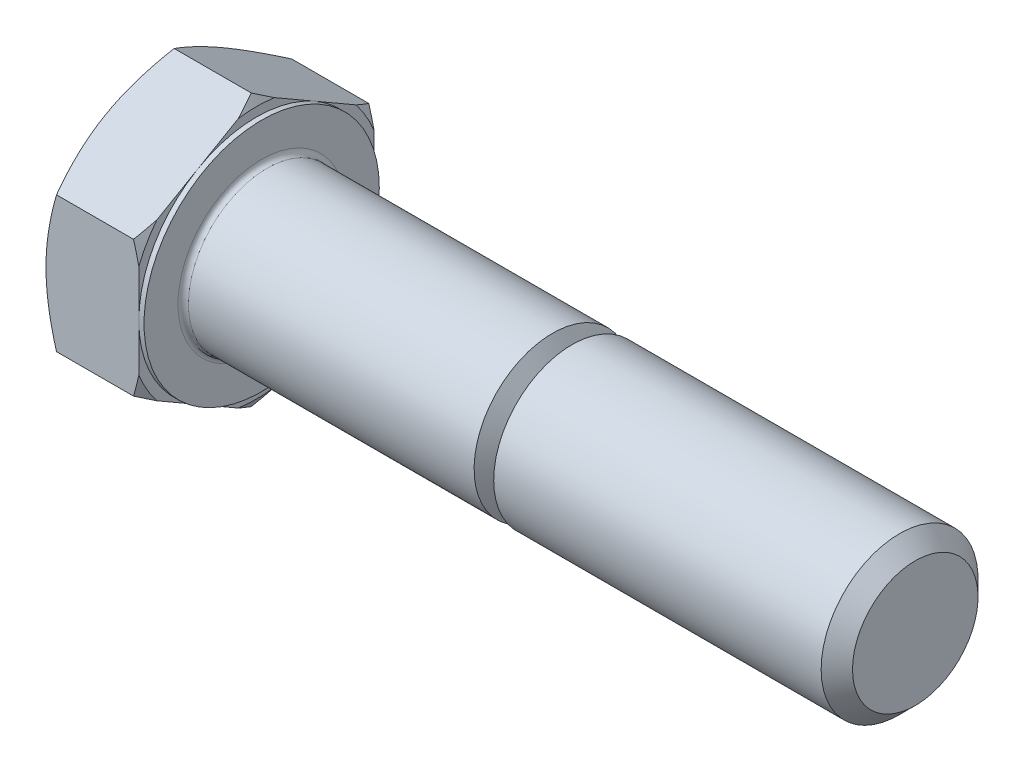
SolidWorks part; units mm, degrees
extrude "基体-拉伸" add sketch "草图1" along normal blind 15
sketch "草图1" plane through (0, 0, 0) normal (1, 0, 0) x (0, 0, -1)
  line L0 (18, 10.3923) -> (18, -10.3923)
  line L1 (-18, 10.3923) -> (-18, -10.3923)
  line L2 (18, -10.3923) -> (0, -20.7846)
  line L3 (0, -20.7846) -> (-18, -10.3923)
  line L4 (18, 10.3923) -> (0, 20.7846)
  line L5 (0, 20.7846) -> (-18, 10.3923)
  dimension "s" = 36
  dimension "D2" = 120
  dimension "D3" = 18
  dimension "D4" = 18
  dimension "D5" = 18
revolve "切除-旋转1" cut sketch "草图3" angle 360 about L6
sketch "草图3" plane through (0, 0, 0) normal (0, 0, 1) x (1, 0, 0)
  line L0 (0, 18) -> (4.4944, 25.7846)
  line L1 (0, 20.7846) -> (0, 10.3923) construction
  line L2 (4.4944, 25.7846) -> (4.4944, 30.7846)
  line L3 (4.4944, 30.7846) -> (-10, 30.7846)
  line L4 (-10, 30.7846) -> (-10, 18)
  line L5 (-10, 18) -> (0, 18)
  line L6 (0, 0) -> (99.06, 0) construction
  line L7 (15, 20.7846) -> (0, 20.7846) construction
  dimension "D1" = 18
  dimension "D2" = 5
  dimension "D3" = 10
  dimension "D4" = 5
  dimension "Head_ch_ang" = 30
ref_plane "前视" through (0, 0, 0) normal (0, 0, 1) x (1, 0, 0)
ref_plane "上视" through (0, 0, 0) normal (0, 1, 0) x (1, 0, 0)
ref_plane "右视" through (0, 0, 0) normal (1, 0, 0) x (0, 0, -1)
sketch "草图2" plane through (0, 0, 0) normal (0, 0, 1) x (1, 0, 0)
  line L0 (0, 10.3923) -> (0, -10.3923) construction
  line L1 (0, 0) -> (115, 0)
  line L2 (0, 0) -> (0, 12)
  line L3 (0, 12) -> (27.8072, 12)
  line L4 (115, 0) -> (115, 9.402)
  line L5 (15, 20.7846) -> (15, 10.3923) construction
  line L7 (0, 0) -> (96.52, 0) construction
  line L8 (115, -9.402) -> (27.8072, -12) construction
  line L9 (0, -12) -> (27.8072, -12) construction
  line L10 (18, 15.24) -> (18, -1.27) construction
  line L11 (61, 15.24) -> (61, -1.27) construction
  line L12 (15, 10.3923) -> (15, -10.3923) construction
  line L13 (27.8072, 12) -> (115, 12)
  line L14 (115, 12) -> (115, 9.402)
revolve "凸台-旋转1" add sketch "草图2" angle 360 about L7
cosmetic thread "螺旋线1" parameters "Thread_length"=54, "Thread_minor"=18.804
sketch "草图5" plane through (0, 0, 0) normal (0, 0, 1) x (1, 0, 0)
  line L0 (15, 18) -> (10.5056, 25.7846)
  line L1 (15, 20.7846) -> (15, 10.3923) construction
  line L2 (10.5056, 25.7846) -> (10.5056, 30.7846)
  line L3 (10.5056, 30.7846) -> (20.5056, 30.7846)
  line L4 (20.5056, 30.7846) -> (20.5056, 18)
  line L5 (20.5056, 18) -> (15, 18)
  line L7 (15, 20.7846) -> (1.6077, 20.7846) construction
  line L8 (0, 0) -> (99.06, 0) construction
  line L9 (0, 0) -> (99.06, 0) construction
  dimension "D1" = 18
  dimension "D2" = 5
  dimension "D3" = 10
  dimension "D4" = 5
revolve "切除-旋转2" cut sketch "草图5" angle 360 about L8
sketch "草图4" plane through (0, 0, 0) normal (0, 0, 1) x (1, 0, 0)
  line L1 (15, 20.7846) -> (15, 10.3923) construction
  line L2 (15, 18) -> (14.2, 18)
  line L3 (15, 18) -> (15, 30.7846)
  line L4 (15, 30.7846) -> (14.2, 30.7846)
  line L5 (0, 0) -> (95.25, 0) construction
  line L6 (0, 0) -> (96.52, 0) construction
  line L7 (14.2, 18) -> (14.2, 30.7846)
  line L8 (13.3923, 20.7846) -> (1.6077, 20.7846) construction
  dimension "D2" = 10
  dimension "D1" = 36
revolve "切除-旋转3" cut sketch "草图4" angle 360 about L5
chamfer "倒角" distance 2.4 angle 45 1 edges at (115, 0, 12)
fillet "圆角" radius 0.8 1 edges at (15, 0, -12)
sketch "草图6" plane through (0, 0, 0) normal (0, 0, 1) x (1, 0, 0)
  line L0 (61, -9.402) -> (59.5, -12)
  line L1 (61, -9.402) -> (62.5, -12)
  line L2 (62.5, -12) -> (62.5, -15)
  line L3 (-3.175, 0) -> (5.1513, 0) construction
  line L5 (62.5, -15) -> (59.5, -15)
  line L6 (59.5, -15) -> (59.5, -12)
  dimension "Thread_minor" = 18.804
  dimension "Diameter" = 24
  dimension "Start" = 61
revolve "切除-旋转4" cut sketch "草图6" angle 360 about L3
pattern_linear "阵列(线性)1" [suppressed]
equation "\"D3@草图1\" = \"s@草图1\" / 2"
equation "\"D4@草图1\" = \"D3@草图1\""
equation "\"D5@草图1\" = \"D4@草图1\""
equation "\"Thread_minor@螺旋线1\" = \"Minor_dia@草图2\""
equation "\"D1@草图3\" = \"s@草图1\" / 2"
equation "\"D1@草图5\" = \"s@草图1\" / 2"
equation "\"Head_ch_ang@草图5\" = \"Head_ch_ang@草图3\""
equation "\"D1@草图4\" = \"s@草图1\""
equation "\"Thread_length@螺旋线1\" = ((sgn( (\"l@草图2\" - \"p@草图2\" ) - \"h@草图2\" )-1)*( (\"l@草图2\" - \"p@草图2\" ) - \"h@草图2\" ))/-2+ \"h@草图2\""
equation "\"Thread_minor@草图6\" = \"Minor_dia@草图2\""
equation "\"Diameter@草图6\" = \"m@草图2\""
equation "\"Overcut@草图6\" = \"m@草图2\" * 1.25"
equation "\"Start@草图6\" = \"k@基体-拉伸\" + \"l@草图2\" - \"Thread_length@螺旋线1\"  '---Non-countersunk---"
equation "\"Num_threads@阵列(线性)1\" = int( \"Thread_length@螺旋线1\" / \"p@草图2\" + 0.999 )  + 1"
equation "\"Advance@阵列(线性)1\" = \"Thread_length@螺旋线1\" /  (\"Num_threads@阵列(线性)1\" - 1) 'relax it"
equation "\"Num_threads@阵列(线性)1\" = \"Num_threads@阵列(线性)1\" - sgn( \"Num_threads@阵列(线性)1\" - 1) '---chamfered tips only---"
equation "\"Minor_dia@草图2\" = \"m@草图2\"-\"p@草图2\" * 1.732"
equation "\"D1@倒角\" = \"p@草图2\"*0.8"
